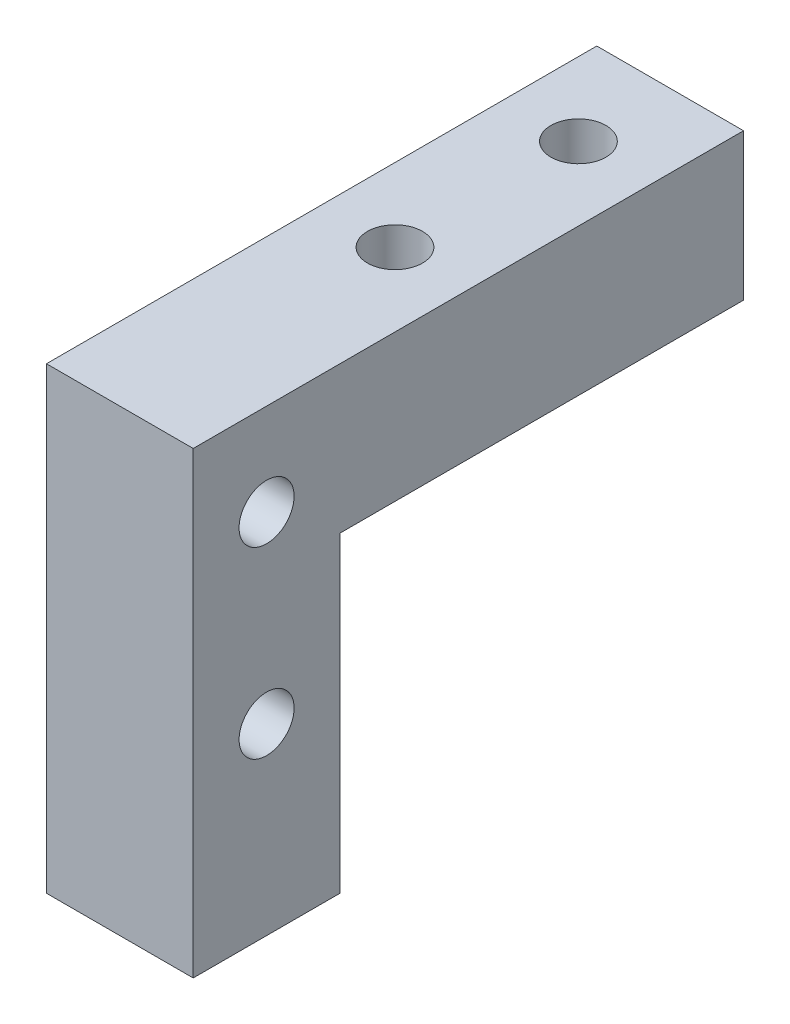
SolidWorks part; units mm, degrees
material "1060 Alloy"
ref_plane "Front Plane" through (0, 0, 0) normal (0, 0, 1) x (1, 0, 0)
ref_plane "Top Plane" through (0, 0, 0) normal (0, 1, 0) x (1, 0, 0)
ref_plane "Right Plane" through (0, 0, 0) normal (1, 0, 0) x (0, 0, -1)
sketch "Sketch1" plane through (0, 0, 0) normal (1, 0, 0) x (0, 0, -1)
  line L0 (0, 0) -> (0, -34)
  line L1 (0, -34) -> (-16, -34)
  line L2 (-16, -34) -> (-16, 16)
  line L3 (-16, 16) -> (44, 16)
  line L4 (44, 16) -> (44, 0)
  line L5 (44, 0) -> (0, 0)
  dimension "D1" = 16
  dimension "D2" = 16
  dimension "D3" = 50
  dimension "D4" = 60
extrude "Boss-Extrude1" add sketch "Sketch1" along normal mid plane 16
sketch "Sketch2" plane through (8, 0, 0) normal (1, 0, 0) x (0, 0, -1)
  line L0 (-8, -34) -> (-8, 18.1584) construction
  line L1 (-16, -34) -> (0, -34) construction
  line L2 (44, 16) -> (-16, 16) construction
  circle A0 centre (-8, 6) radius 3
  circle A1 centre (-8, -14) radius 3
  dimension "D1" = 6
  dimension "D2" = 6
  dimension "D3" = 20
  dimension "D4" = 10
extrude "Cut-Extrude1" cut sketch "Sketch2" against normal through all
sketch "Sketch3" plane through (0, 16, 0) normal (0, 1, 0) x (1, 0, 0)
  line L0 (0, -16) -> (0, 45.1263) construction
  line L1 (8, -16) -> (-8, -16) construction
  line L2 (8, 44) -> (-8, 44) construction
  circle A0 centre (0, 34) radius 3
  circle A1 centre (0, 14) radius 3
  dimension "D1" = 6
  dimension "D2" = 6
  dimension "D3" = 20
  dimension "D4" = 10
extrude "Cut-Extrude2" cut sketch "Sketch3" against normal through all
